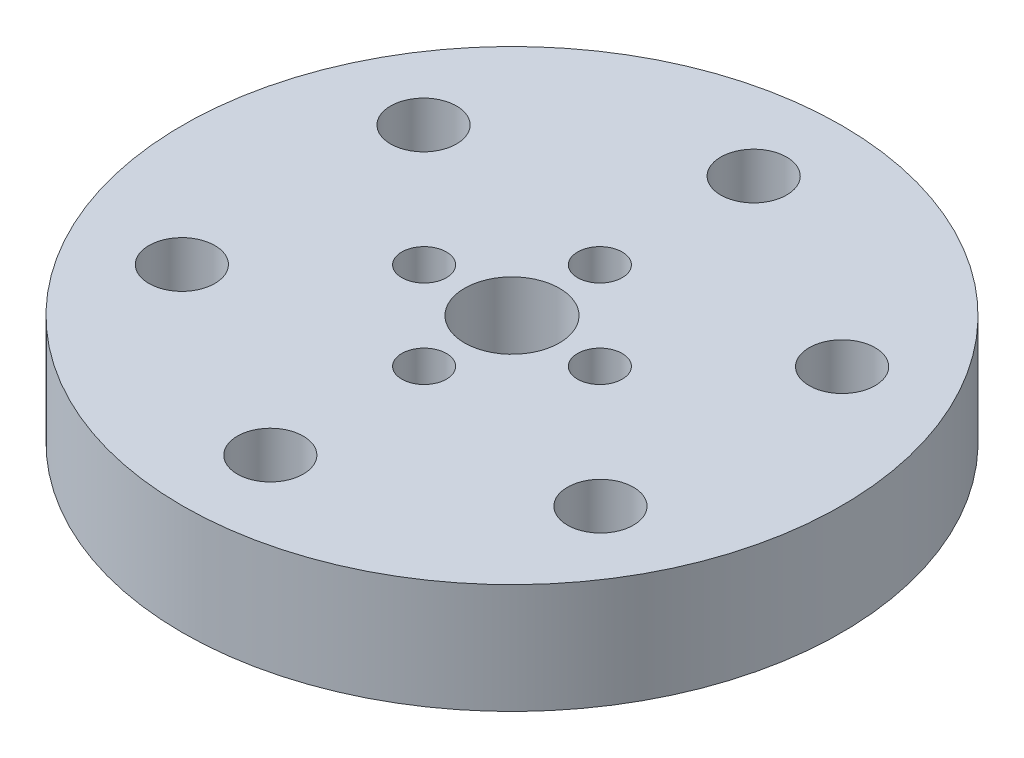
SolidWorks part; units mm, degrees
ref_plane "Front Plane" through (0, 0, 0) normal (0, 0, 1) x (1, 0, 0)
ref_plane "Top Plane" through (0, 0, 0) normal (0, 1, 0) x (1, 0, 0)
ref_plane "Right Plane" through (0, 0, 0) normal (1, 0, 0) x (0, 0, -1)
sketch "Sketch1" plane through (0, 0, 0) normal (0, 1, 0) x (1, 0, 0)
  circle A0 centre (0, 0) radius 30
  dimension "D1" = 60
extrude "Boss-Extrude1" add sketch "Sketch1" along normal blind 10
sketch "Sketch2" plane through (0, 10, 0) normal (0, 1, 0) x (1, 0, 0)
  circle A0 centre (0, -22) radius 3
  circle A1 centre (-19.0526, -11) radius 3
  circle A2 centre (-19.0526, 11) radius 3
  circle A3 centre (0, 22) radius 3
  circle A4 centre (19.0526, 11) radius 3
  circle A5 centre (19.0526, -11) radius 3
  point P15 (0, 0)
  dimension "D2" = 6
  dimension "D1" = 22
  dimension "D3" = 6
extrude "Cut-Extrude1" cut sketch "Sketch2" against normal blind 10 contours A2
sketch "Sketch4" plane through (0, 10, 0) normal (0, 1, 0) x (1, 0, 0)
  circle A0 centre (0, 0) radius 4.318
  circle A1 centre (0, -8.001) radius 2.032
  circle A2 centre (-8.001, 0) radius 2.032
  circle A3 centre (0, 8.001) radius 2.032
  circle A4 centre (8.001, 0) radius 2.032
  point P14 (0, 0)
  dimension "D1" = 8.001
  dimension "D2" = 4
extrude "Cut-Extrude2" cut sketch "Sketch4" against normal blind 10
